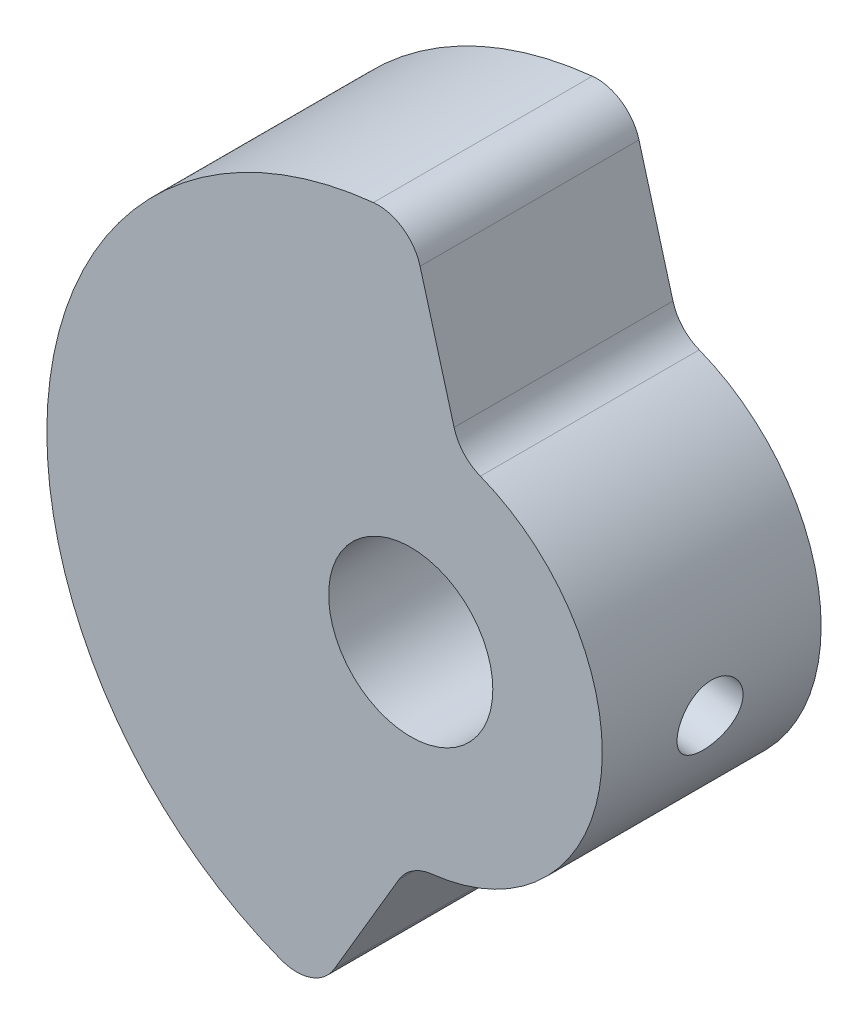
SolidWorks part; units mm, degrees
material "6061-T6 (SS)"
ref_plane "Front Plane" through (0, 0, 0) normal (0, 0, 1) x (1, 0, 0)
ref_plane "Top Plane" through (0, 0, 0) normal (0, 1, 0) x (1, 0, 0)
ref_plane "Right Plane" through (0, 0, 0) normal (1, 0, 0) x (0, 0, -1)
sketch "Sketch1" plane through (0, 0, 0) normal (0, 0, 1) x (1, 0, 0)
  line L0 (0, 0) -> (0, 4.953) construction
  line L1 (0, -21.1125) -> (0, 21.1125) construction
  line L2 (-5.4643, -20.3931) -> (5.4643, 20.3931) construction
  line L3 (0, -11.1125) -> (-5.4643, -20.3931)
  line L4 (0, 21.1125) -> (2.8761, 10.7339)
  circle A0 centre (0, 0) radius 4.7625
  arc A1 (0, -11.1125) -> (1.6622, 10.9875) centre (0, 0) ccw
  circle A2 centre (0, 0) radius 21.1125 construction
  circle A3 centre (0, 0) radius 11.1125 construction
  arc A4 (0, 21.1125) -> (-5.4643, -20.3931) centre (0, 0) ccw
  dimension "D1" = 9.525
  dimension "D5" = 10
  dimension "D3" = 4.953
  dimension "D4" = 15
extrude "Boss-Extrude1" add sketch "Sketch1" along normal blind 12.7
fillet "Fillet1" radius 2.54 4 edges at (0, -11.1125, 6.35) (2.8761, 10.7339, 6.35) (-5.4643, -20.3931, 6.35) (0, 21.1125, 6.35)
hole_wizard "#10-24 Tapped Hole1" positions "3DSketch2" profile "Sketch2" tap size "#10-24" standard "ANSI Inch"
sketch3d "3DSketch2"
  line L0 (0, 0, 0) -> (11.0192, -1.437, 0) construction
  line L1 (11.0192, -1.437, 0) -> (11.0193, -1.4366, 12.7) construction
  arc A0 (1.2216, -11.0452, 0) -> (4.0386, 10.3526, 0) centre (0, 0, 0) ccw construction
  arc A1 (1.2216, -11.0452, 12.7) -> (4.0386, 10.3526, 12.7) centre (0, 0, 12.7) ccw construction
  point P0 (11.0192, -1.4368, 6.35)
  point P9 (0, 0, 11.1125)
  point P14 (0, 0, 23.8125)
sketch "Sketch2" plane through (11.0192, -1.4368, 6.35) normal (0, 0, 1) x (0.1293, 0.9916, 0)
  line L0 (0, 0) -> (0, 6.35)
  line L1 (0, 6.35) -> (1.8986, 6.35)
  line L2 (1.8986, 6.35) -> (1.8986, 0)
  line L5 (1.8986, 0) -> (0, 0)
  line L11 (0, -6.35) -> (0, 107.95) construction
  dimension "Thru Tap Drill Dia." = 3.7973
  dimension "Thru Tap Drill Depth" = 6.35
cosmetic thread "Hole Thread1" parameters "D2"=4.826
